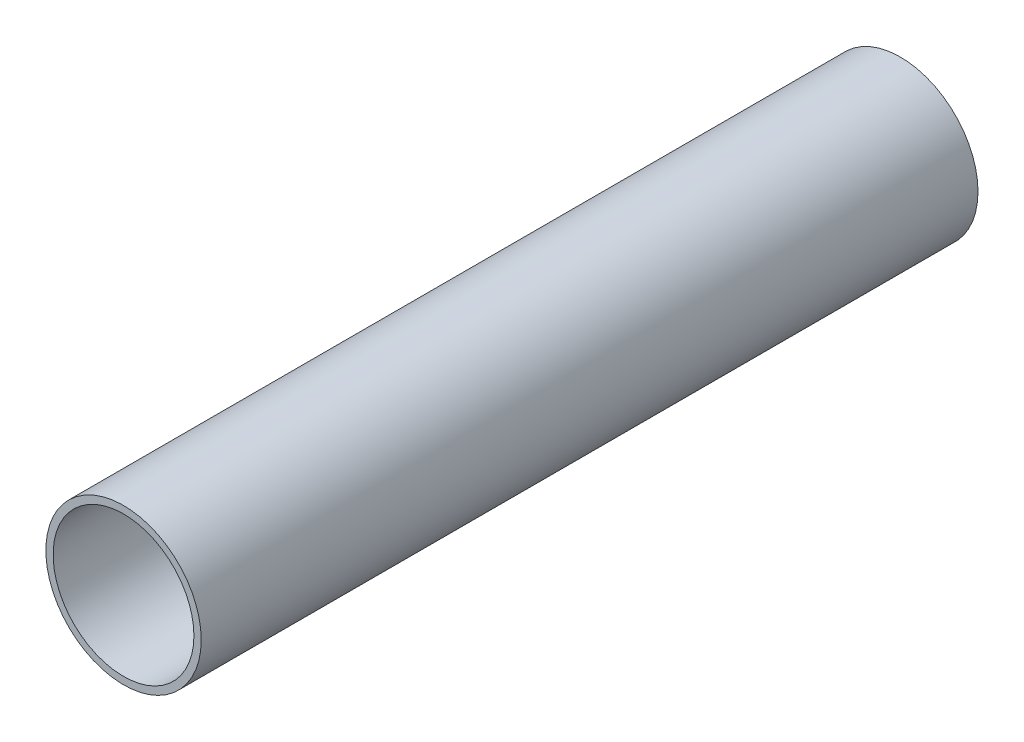
SolidWorks part; units mm, degrees
material "5052 Alloy"
ref_plane "Front Plane" through (0, 0, 0) normal (0, 0, 1) x (1, 0, 0)
ref_plane "Top Plane" through (0, 0, 0) normal (0, 1, 0) x (1, 0, 0)
ref_plane "Right Plane" through (0, 0, 0) normal (1, 0, 0) x (0, 0, -1)
sketch "Sketch1" plane through (0, 0, 0) normal (0, 0, 1) x (1, 0, 0)
  circle A0 centre (0, 0) radius 8
  dimension "D1" = 16
extrude "Extrude1" add sketch "Sketch1" against normal blind 80
sketch "Sketch2" plane through (0, 0, 0) normal (0, 0, 1) x (1, 0, 0)
  circle A0 centre (0, 0) radius 7.25
  dimension "D1" = 14.5
extrude "Cut-Extrude1" cut sketch "Sketch2" against normal through all
